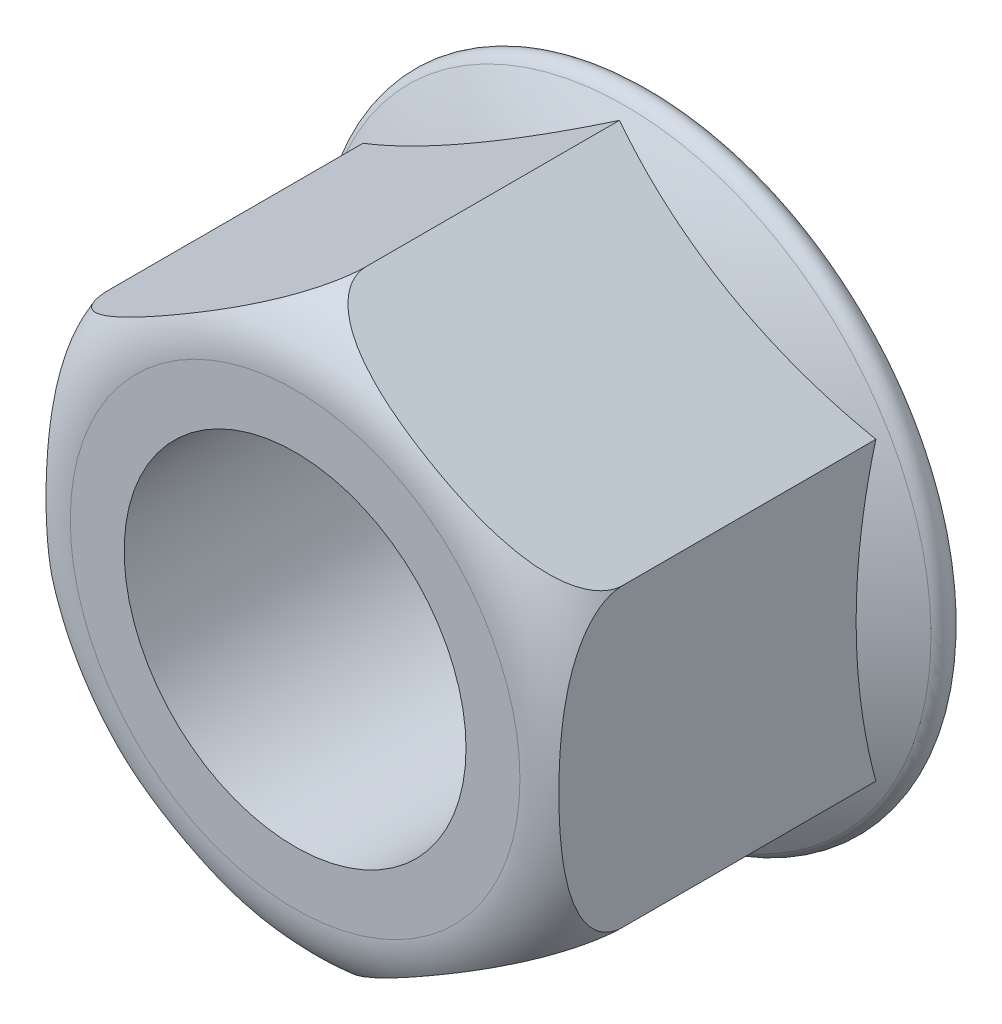
SolidWorks part; units mm, degrees
ref_plane "Plane1" through (0, 0, 0) normal (0, 0, 1) x (1, 0, 0)
ref_plane "Plane2" through (0, 0, 0) normal (0, 1, 0) x (-1, 0, 0)
ref_plane "Plane3" through (0, 0, 0) normal (1, 0, 0) x (0, 0, -1)
other "Configuration Table"
sketch "Head Sketch" plane through (0, 0, 0) normal (0, 0, 1) x (1, 0, 0)
  line L0 (0, 10.5586) -> (9.144, 5.2793)
  line L1 (9.144, 5.2793) -> (9.144, -5.2793)
  line L2 (9.144, -5.2793) -> (0, -10.5586)
  line L3 (0, -10.5586) -> (-9.144, -5.2793)
  line L4 (-9.144, -5.2793) -> (-9.144, 5.2793)
  line L5 (-9.144, 5.2793) -> (0, 10.5586)
  line L6 (9.144, 5.2793) -> (-9.144, -5.2793) construction
  line L7 (0, 10.5586) -> (0, -10.5586) construction
  line L8 (-9.144, 5.2793) -> (9.144, -5.2793) construction
  point P0 (0, 0)
  dimension "D1" = 60
  dimension "D2" = 60
  dimension "Flats" = 18.288
extrude "Head" add sketch "Head Sketch" along normal blind 12.7
sketch "Flange Sketch" plane through (0, 0, 0) normal (0, 1, 0) x (-1, 0, 0)
  line L0 (0, 1.8434) -> (0, 3.81) construction
  line L1 (-10.668, 0) -> (0, 0)
  line L2 (0, 50) -> (0, -50) construction
  line L4 (0, 0) -> (0, 3.81)
  line L5 (0, 0) -> (-9.144, 0) construction
  arc A0 (0, 3.81) -> (-10.9143, 0.9351) centre (0, -18.3452) ccw
  arc A1 (-10.668, 0) -> (-10.9143, 0.9351) centre (-10.668, 0.5) cw
  dimension "D1" = 0.5
  dimension "D3" = 21.336
  dimension "Flange Height" = 3.81
revolve "Flange" add sketch "Flange Sketch" angle 360 about L0
sketch "Sketch5" plane through (0, 0, 0) normal (1, 0, 0) x (0, 0, -1)
  line L0 (-12.7, -8.0186) -> (-12.7, -10.5586)
  line L1 (-12.7, -10.5586) -> (-10.16, -10.5586)
  line L2 (-12.7, -10.5586) -> (-1.1322, -10.5586) construction
  line L3 (-12.7, -10.5586) -> (-12.7, -5.2793) construction
  line L5 (-15.0856, 0) -> (-8.1394, 0) construction
  line L6 (50, 0) -> (-50, 0) construction
  arc A0 (-12.7, -8.0186) -> (-10.16, -10.5586) centre (-10.16, -8.0186) ccw
  dimension "D1" = 2.54
revolve "Head Trim" cut sketch "Sketch5" angle 360 about L5
sketch "Hole Sketch" plane through (0, 0, 12.7) normal (0, 0, 1) x (1, 0, 0)
  line L0 (50, 0) -> (-50, 0) construction
  line L1 (0, -50) -> (0, 50) construction
  circle A0 centre (0, 0) radius 6.096
  dimension "Hole Dia" = 12.192
extrude "Through Hole" cut sketch "Hole Sketch" against normal through all
cosmetic thread "Cosmetic Thread1" parameters "D2"=28.592
